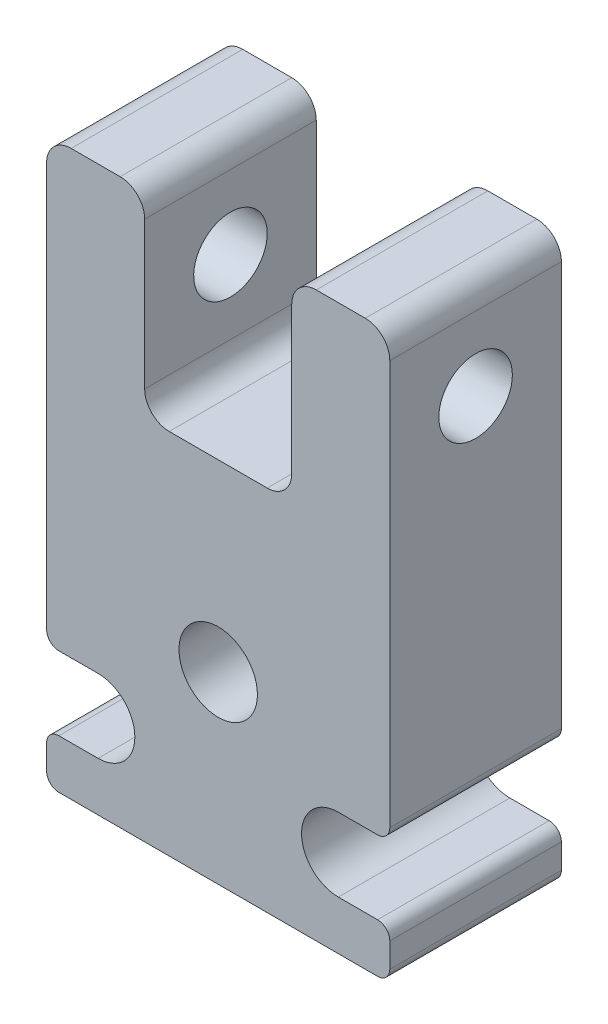
SolidWorks part; units mm, degrees
ref_plane "Alzado" through (0, 0, 0) normal (0, 0, 1) x (1, 0, 0)
ref_plane "Planta" through (0, 0, 0) normal (0, 1, 0) x (1, 0, 0)
ref_plane "Vista lateral" through (0, 0, 0) normal (1, 0, 0) x (0, 0, -1)
sketch "Croquis1" plane through (0, 0, 0) normal (0, 0, 1) x (1, 0, 0)
  line L0 (3, 11.5) -> (7, 11.5)
  line L1 (-7, 11.5) -> (-3, 11.5)
  line L2 (-7, 11.5) -> (-7, -6.5)
  line L3 (-7, -11.5) -> (7, -11.5)
  line L4 (7, 11.5) -> (7, -6.5)
  line L5 (-7, 11.5) -> (7, -11.5) construction
  line L6 (-7, -11.5) -> (7, 11.5) construction
  line L7 (-3, 11.5) -> (3, 11.5) construction
  line L8 (-3, 11.5) -> (-3, 3.5)
  line L9 (-3, 3.5) -> (3, 3.5)
  line L10 (3, 11.5) -> (3, 3.5)
  line L11 (0, 0) -> (0, -11.5) construction
  line L12 (4.9, -6.5) -> (7, -6.5)
  line L13 (4.9, -9.5) -> (7, -9.5)
  line L14 (-4.9, -6.5) -> (-7, -6.5)
  line L15 (-4.9, -9.5) -> (-7, -9.5)
  line L16 (-7, -9.5) -> (-7, -11.5)
  line L17 (7, -9.5) -> (7, -11.5)
  arc A1 (4.9, -6.5) -> (4.9, -9.5) centre (4.9, -8) ccw
  arc A2 (-4.9, -9.5) -> (-4.9, -6.5) centre (-4.9, -8) ccw
  circle A3 centre (0, -4) radius 1.6
  point P0 (0, 0)
  point P10 (0, 3.5)
  point P14 (-3.4, -8)
  point P16 (3.4, -8)
  point P17 (6.4, -8)
  point P19 (4.9, -9.5)
  point P29 (0, -5.6)
  dimension "D5" = 4
  dimension "D7" = 3
  dimension "D6" = 3.2
  dimension "D1" = 14
  dimension "D2" = 23
  dimension "D3" = 6
  dimension "D4" = 8
  dimension "D8" = 9.8
  dimension "D9" = 2
extrude "Saliente-Extruir1" add sketch "Croquis1" along normal mid plane 7
sketch "Croquis2" plane through (0, 0, 0) normal (1, 0, 0) x (0, 0, -1)
  line L0 (-3.5, 11.5) -> (3.5, 11.5) construction
  circle A0 centre (0, 7.5) radius 1.5
  dimension "D1" = 3
  dimension "D2" = 4
extrude "Cortar-Extruir1" cut sketch "Croquis2" against normal through all both and the other way through all
fillet "Redondeo1" radius 1 6 edges at (-7, 11.5, 0) (-3, 11.5, 0) (-3, 3.5, 0) (3, 3.5, 0) (3, 11.5, 0) (7, 11.5, 0)
fillet "Redondeo2" radius 0.5 6 edges at (7, -11.5, 0) (-7, -11.5, 0) (7, -9.5, 0) (7, -6.5, 0) (-7, -9.5, 0) (-7, -6.5, 0)
